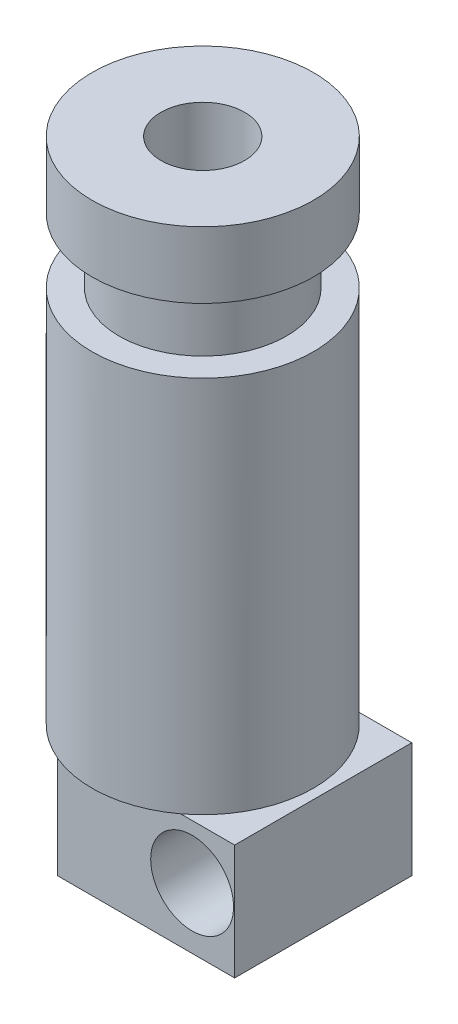
SolidWorks part; units mm, degrees
ref_plane "Front Plane" through (0, 0, 0) normal (0, 0, 1) x (1, 0, 0)
ref_plane "Top Plane" through (0, 0, 0) normal (0, 1, 0) x (1, 0, 0)
ref_plane "Right Plane" through (0, 0, 0) normal (1, 0, 0) x (0, 0, -1)
sketch "Sketch1" plane through (0, 0, 0) normal (0, 1, 0) x (1, 0, 0)
  circle A0 centre (0, 0) radius 7.9375
extrude "Boss-Extrude1" add sketch "Sketch1" along normal blind 27.1
sketch "Sketch2" plane through (0, 27.1, 0) normal (0, 1, 0) x (1, 0, 0)
  circle A0 centre (0, 0) radius 3
extrude "Cut-Extrude1" cut sketch "Sketch2" against normal blind 36.5
sketch "Sketch3" plane through (0, 27.1, 0) normal (0, 1, 0) x (1, 0, 0)
  circle A0 centre (0, 0) radius 6
extrude "Boss-Extrude2" add sketch "Sketch3" along normal blind 4.64
sketch "Sketch4" plane through (0, 31.74, 0) normal (0, 1, 0) x (1, 0, 0)
  circle A0 centre (0, 0) radius 7.9375
extrude "Boss-Extrude3" add sketch "Sketch4" along normal blind 4.76
sketch "Sketch5" plane through (0, 0, 0) normal (0, -1, 0) x (1, 0, 0)
  circle A0 centre (0, 0) radius 3
extrude "Cut-Extrude2" cut sketch "Sketch5" against normal blind 81.214
sketch "Sketch8" plane through (0, 0, 0) normal (0, -1, 0) x (1, 0, 0)
  line L1 (-4.064, -6.35) -> (8.636, -6.35)
  line L2 (-4.064, -6.35) -> (-4.064, 6.35)
  line L3 (-4.064, 6.35) -> (8.636, 6.35)
  line L4 (8.636, -6.35) -> (8.636, 6.35)
  dimension "D1" = 12.7
  dimension "D2" = 12.7
  dimension "D3" = 6.35
  dimension "D4" = 4.064
extrude "Boss-Extrude5" add sketch "Sketch8" along normal blind 8.255
sketch "Sketch11" plane through (0, -8.255, 0) normal (0, -1, 0) x (1, 0, 0)
  circle A0 centre (0, 0) radius 3.9688
extrude "Boss-Extrude7" add sketch "Sketch11" along normal blind 1.27
sketch "Sketch12" plane through (0, -9.525, 0) normal (0, -1, 0) x (-1, 0, 0)
  circle A0 centre (0, 0) radius 3.9688
extrude "Boss-Extrude8" add sketch "Sketch12" along normal blind 1.778 draft 65
sketch "Sketch13" plane through (0, 0, -6.35) normal (0, 0, -1) x (-1, 0, 0)
  line L0 (-8.636, -8.255) -> (-8.636, 0) construction
  circle A0 centre (-5.588, -3.8881) radius 2.9718
  dimension "D1" = 3.048
extrude "Cut-Extrude9" cut sketch "Sketch13" against normal blind 25.4
sketch "Sketch14" plane through (0, 36.5, 0) normal (0, 1, 0) x (1, 0, 0)
  circle A0 centre (0, 0) radius 0.02
extrude "Cut-Extrude10" cut sketch "Sketch14" against normal blind 254
